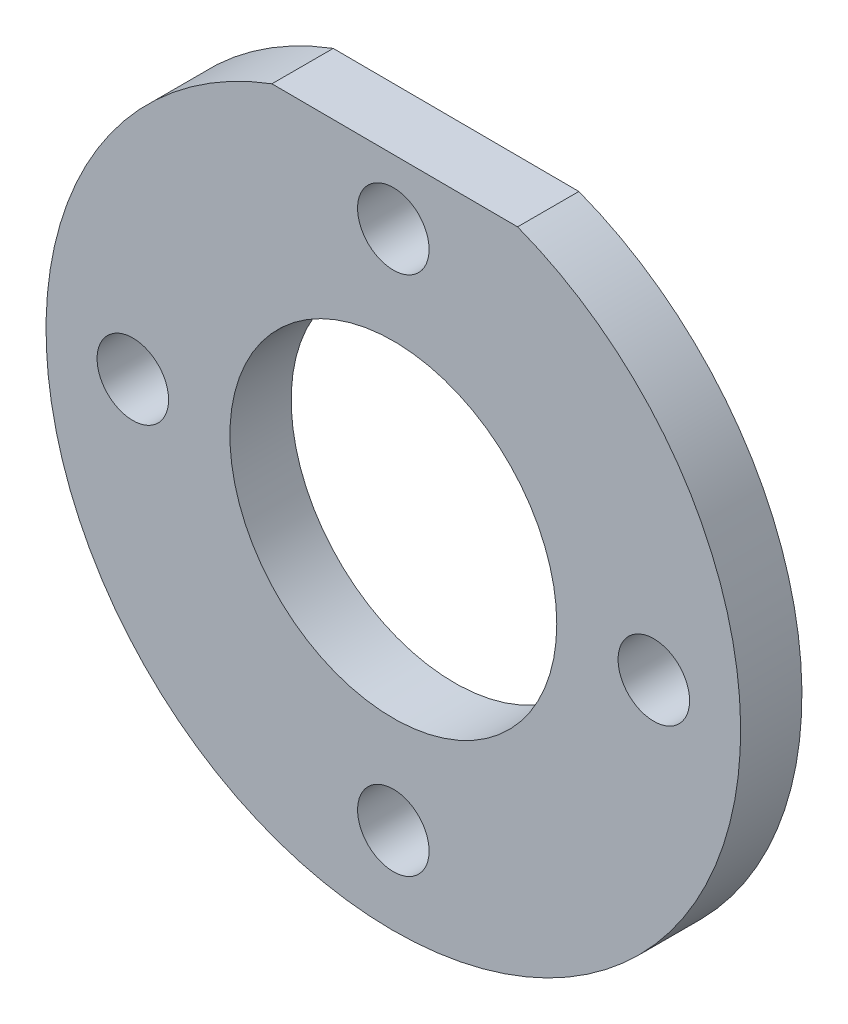
SolidWorks part; units mm, degrees
ref_plane "Plano frontal" through (0, 0, 0) normal (0, 0, 1) x (1, 0, 0)
ref_plane "Plano superior" through (0, 0, 0) normal (0, 1, 0) x (1, 0, 0)
ref_plane "Plano direito" through (0, 0, 0) normal (1, 0, 0) x (0, 0, -1)
sketch "Esboço1" plane through (0, 0, 0) normal (0, 0, 1) x (1, 0, 0)
  circle A0 centre (0, 0) radius 34
  circle A1 centre (0, 0) radius 16
  circle A2 centre (0, 0) radius 25.5 construction
  circle A3 centre (0, 25.5) radius 3.5
  circle A4 centre (25.5, 0) radius 3.5
  circle A5 centre (0, -25.5) radius 3.5
  circle A6 centre (-25.5, 0) radius 3.5
  point P16 (0, 0)
  dimension "D1" = 7
  dimension "D2" = 51
  dimension "D3" = 68
  dimension "D4" = 32
  dimension "D5" = 4
extrude "Ressalto-extrusão1" add sketch "Esboço1" along normal blind 6
sketch "Esboço2" plane through (0, 0, 6) normal (0, 0, 1) x (1, 0, 0)
  line L0 (-11.8841, 31.8554) -> (12.163, 31.75)
  circle A0 centre (0, 0) radius 34 construction
  arc A1 (-11.8841, 31.8554) -> (12.163, 31.75) centre (0, 0) cw
extrude "Corte-extrusão1" cut sketch "Esboço2" against normal blind 10
